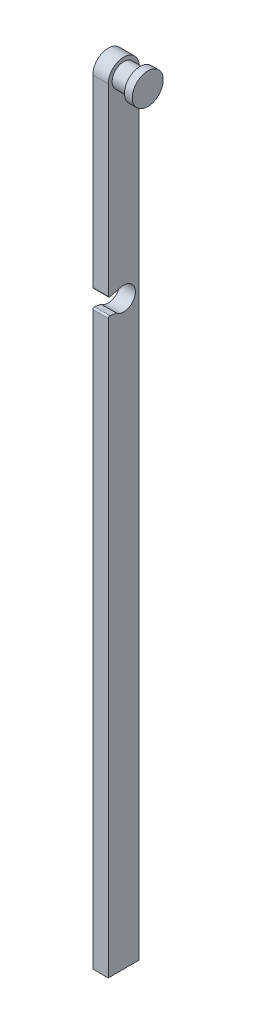
SolidWorks part; units mm, degrees
ref_plane "Plan de face" through (0, 0, 0) normal (0, 0, 1) x (1, 0, 0)
ref_plane "Plan de dessus" through (0, 0, 0) normal (0, 1, 0) x (1, 0, 0)
ref_plane "Plan de droite" through (0, 0, 0) normal (1, 0, 0) x (0, 0, -1)
sketch "Esquisse1" plane through (0, 0, 0) normal (1, 0, 0) x (0, 0, -1)
  line L0 (-1.1935, 29.8363) -> (-2, 50) construction
  line L2 (2, 50) -> (2, -50)
  line L3 (2, -50) -> (-2, -50)
  line L4 (-2, 50) -> (-2, -50)
  line L5 (2, 50) -> (1.1935, 29.8363) construction
  line L6 (2, -50) -> (0, 0) construction
  line L7 (0, 0) -> (-2, -50) construction
  arc A0 (2, 50) -> (-2, 50) centre (0, 50) ccw
  point P0 (0, 0)
  point P6 (0, 40)
  dimension "D1" = 4
  dimension "D2" = 100
extrude "BASE" add sketch "Esquisse1" along normal blind 2
sketch "Esquisse2" plane through (2, 0, 0) normal (1, 0, 0) x (0, 0, -1)
  line L0 (-2, 50) -> (2, 50) construction
  line L1 (2, 50) -> (0, 52) construction
  line L2 (0, 52) -> (0, 39.6014) construction
  arc A0 (2, 50) -> (-2, 50) centre (0, 50) ccw construction
  circle A1 centre (0, 50) radius 1.5
  dimension "D1" = 3
extrude "BOSS FIX" add sketch "Esquisse2" along normal blind 2.1
sketch "Esquisse3" plane through (4.1, 0, 0) normal (1, 0, 0) x (0, 0, -1)
  circle A0 centre (0, 50) radius 2
  dimension "D1" = 4
extrude "BOSS BLOCAGE" add sketch "Esquisse3" along normal blind 1
sketch "Esquisse4" plane through (0, 0, 0) normal (-1, 0, 0) x (0, 0, 1)
  line L0 (0, 25) -> (0, 27.5) construction
  line L1 (0, 27.5) -> (0.3796, 27.5) construction
  line L3 (0.3796, 27.5) -> (0, 25) construction
  line L4 (0, 25) -> (0, 22.5) construction
  line L5 (0, 22.5) -> (2, 22.5) construction
  line L6 (2, 22.5) -> (0, 25) construction
  line L7 (-2, 50) -> (2, 50) construction
  line L8 (0, 50) -> (0, 0) construction
  line L9 (0.2252, 26.483) -> (2, 26)
  line L10 (2, 50) -> (2, -50) construction
  line L11 (2, 26) -> (2, 24)
  line L12 (2, 24) -> (0.937, 23.8287)
  arc A0 (0.2252, 26.483) -> (0.937, 23.8287) centre (0, 25) ccw
  arc A1 (2, 50) -> (-2, 50) centre (0, 50) ccw construction
  point P7 (0, 50)
  point P23 (0, 25)
  dimension "D1" = 3
  dimension "D2" = 2.5
  dimension "D3" = 2.5
  dimension "D4" = 1
  dimension "D5" = 1
extrude "VIDE TIGE" cut sketch "Esquisse4" against normal up to surface (2 mm away) up to face at (2, 0.5, 0)
fillet "CONGE TIGE" radius 0.2 2 edges at (1, 26, 2) (1, 24, 2)
